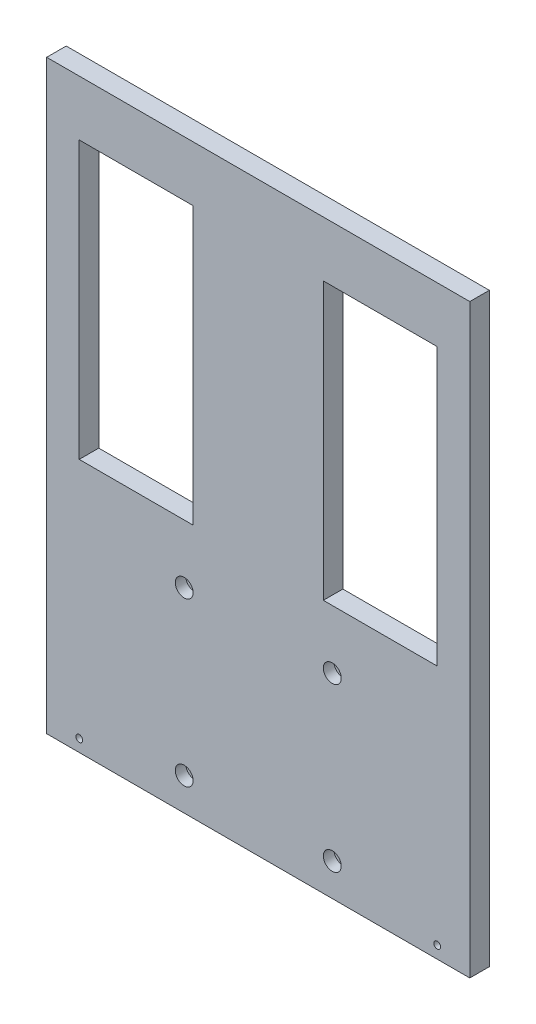
SolidWorks part; units mm, degrees
material "6061 合金"
ref_plane "前视基准面" through (0, 0, 0) normal (0, 0, 1) x (1, 0, 0)
ref_plane "上视基准面" through (0, 0, 0) normal (0, 1, 0) x (1, 0, 0)
ref_plane "右视基准面" through (0, 0, 0) normal (1, 0, 0) x (0, 0, -1)
other "Configuration Table"
sketch "Sketch1" plane through (0, 0, 0) normal (0, 0, 1) x (1, 0, 0)
  line L1 (-130, 174) -> (130, 174)
  line L2 (-130, 174) -> (-130, 534)
  line L3 (-130, 534) -> (130, 534)
  line L4 (130, 174) -> (130, 534)
extrude "Boss-Extrude1" add sketch "Sketch1" along normal blind 12
sketch "Sketch2" plane through (0, 0, 0) normal (0, 0, 1) x (1, 0, 0)
  circle A0 centre (-45.5, 194) radius 3.3
  circle A1 centre (-45.5, 294) radius 3.3
  circle A2 centre (45.5, 194) radius 3.3
  circle A3 centre (45.5, 294) radius 3.3
extrude "Cut-Extrude1" cut sketch "Sketch2" against normal through all and the other way through all
ref_plane "Plane1" through (0, 0, 12) normal (0, 0, 1) x (1, 0, 0)
sketch "Sketch3" plane through (0, 0, 12) normal (0, 0, 1) x (1, 0, 0)
  circle A0 centre (-45.5, 194) radius 5.5
  circle A1 centre (-45.5, 294) radius 5.5
  circle A2 centre (45.5, 194) radius 5.5
  circle A3 centre (45.5, 294) radius 5.5
extrude "Cut-Extrude3" cut sketch "Sketch3" against normal blind 6.5
sketch "Sketch4" plane through (0, 0, 0) normal (0, 0, 1) x (1, 0, 0)
  circle A0 centre (-110, 181.5) radius 2.1
  circle A1 centre (110, 181.5) radius 2.1
extrude "Cut-Extrude4" cut sketch "Sketch4" against normal through all and the other way through all
sketch "Sketch5" plane through (0, 0, 0) normal (0, 0, 1) x (1, 0, 0)
  line L1 (-110, 330) -> (-40, 330)
  line L2 (-110, 330) -> (-110, 500)
  line L3 (-110, 500) -> (-40, 500)
  line L4 (-40, 330) -> (-40, 500)
  line L6 (40, 330) -> (110, 330)
  line L7 (40, 330) -> (40, 500)
  line L8 (40, 500) -> (110, 500)
  line L9 (110, 330) -> (110, 500)
extrude "Cut-Extrude5" cut sketch "Sketch5" against normal through all and the other way through all
